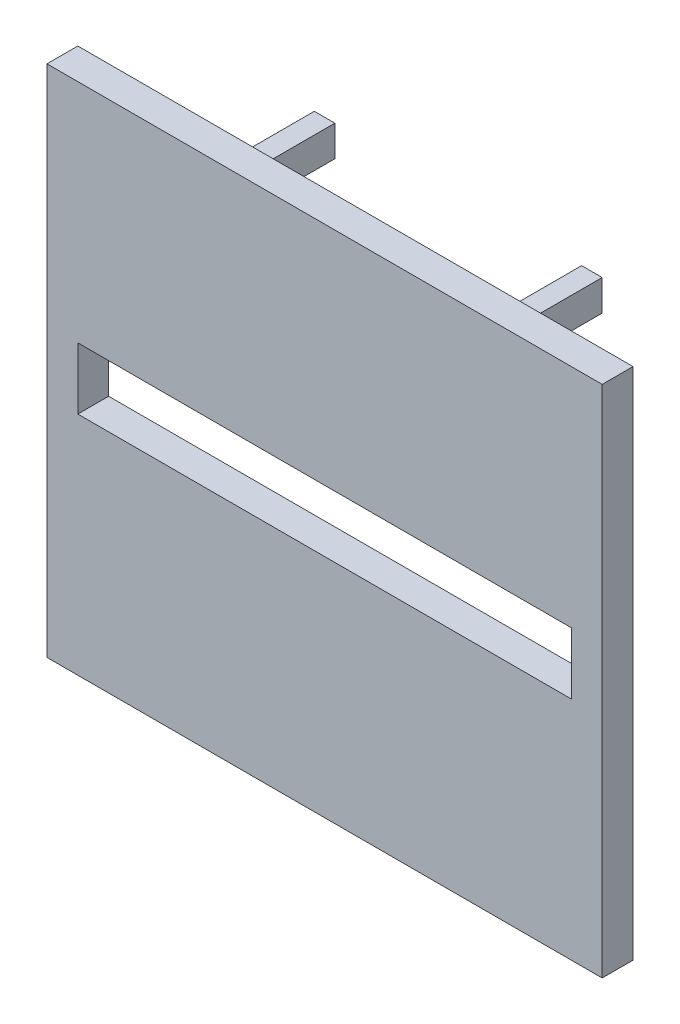
SolidWorks part; units mm, degrees
ref_plane "Front Plane" through (0, 0, 0) normal (0, 0, 1) x (1, 0, 0)
ref_plane "Top Plane" through (0, 0, 0) normal (0, 1, 0) x (1, 0, 0)
ref_plane "Right Plane" through (0, 0, 0) normal (1, 0, 0) x (0, 0, -1)
sketch "Sketch1" plane through (0, 0, 0) normal (0, 0, 1) x (1, 0, 0)
  line L0 (54, 25) -> (0, 25) construction
  line L1 (0, 50) -> (54, 50)
  line L2 (0, 50) -> (0, 0)
  line L3 (0, 0) -> (54, 0)
  line L4 (54, 50) -> (54, 0)
  line L5 (27, 25) -> (27, 50) construction
  line L7 (51, 28) -> (51, 22)
  line L8 (51, 22) -> (3, 22)
  line L9 (3, 22) -> (3, 28)
  line L10 (3, 28) -> (51, 28)
  dimension "D1" = 54
  dimension "D2" = 50
  dimension "D3" = 6
extrude "Boss-Extrude1" add sketch "Sketch1" along normal blind 3
sketch "Sketch2" plane through (0, 0, 0) normal (0, 0, -1) x (-1, 0, 0)
  line L0 (-27, 0) -> (-27, 50) construction
  line L1 (-15, 7) -> (-13, 7)
  line L2 (-41, 7) -> (-13, 7) construction
  line L3 (-13, 7) -> (-13, 4)
  line L4 (-13, 4) -> (-15, 4)
  line L5 (-15, 4) -> (-15, 7)
  line L6 (-3, 22) -> (-51, 22) construction
  line L7 (-41, 7) -> (-41, 4)
  line L8 (-41, 4) -> (-39, 4)
  line L9 (-39, 4) -> (-39, 7)
  line L10 (-39, 7) -> (-41, 7)
  line L11 (-41, 4) -> (-41, 46)
  line L12 (0, 0) -> (-54, 0) construction
  line L13 (-54, 50) -> (0, 50) construction
  line L14 (-41.1655, 7.1412) -> (-41.1655, 4.1412)
  line L15 (-41.1655, 4.1412) -> (-39.1655, 4.1412)
  line L16 (-39.1655, 4.1412) -> (-39.1655, 7.1412)
  line L17 (-39.1655, 7.1412) -> (-41.1655, 7.1412)
  line L18 (-41, 46) -> (-41, 43)
  line L19 (-41, 43) -> (-39, 43)
  line L20 (-39, 43) -> (-39, 46)
  line L21 (-39, 46) -> (-41, 46)
  line L22 (-41, 46) -> (-13, 46) construction
  line L23 (-13, 46) -> (-13, 43)
  line L24 (-13, 43) -> (-15, 43)
  line L25 (-15, 43) -> (-15, 46)
  line L26 (-15, 46) -> (-13, 46)
  dimension "D1" = 28
  dimension "D2" = 3
  dimension "D3" = 2
  dimension "D4" = 15
  dimension "D5" = 3
  dimension "D6" = 2
  dimension "D7" = 42
  dimension "D8" = 2
  dimension "D9" = 3
extrude "Boss-Extrude2" add sketch "Sketch2" along normal blind 10 contours L20 L21 L11 L19 | L26 L25 L24 L23 | L15 L16 L10 L7 | L5 L4 L3 L1
